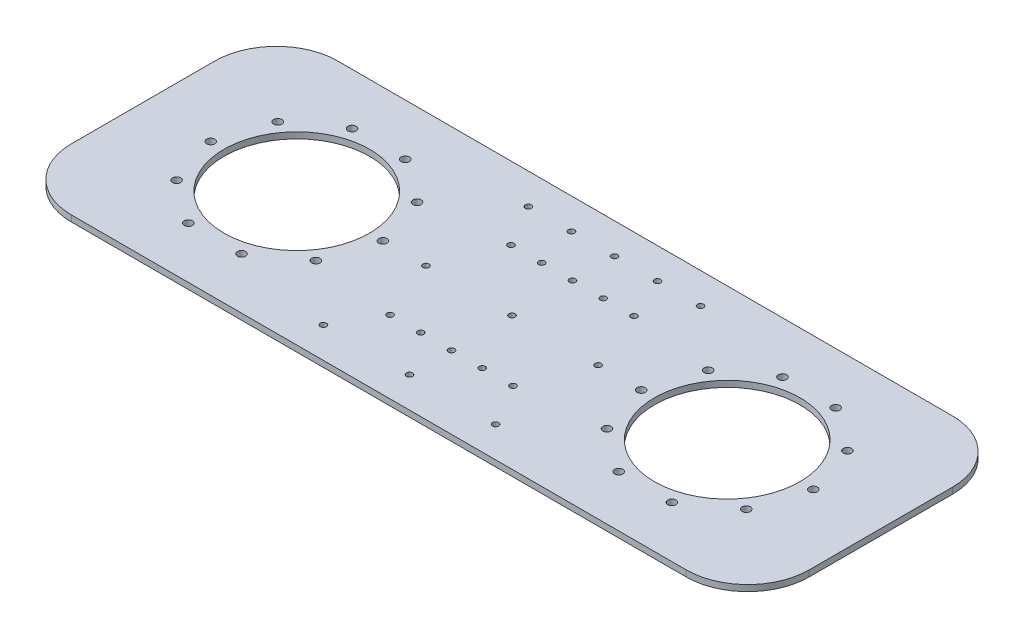
SolidWorks part; units mm, degrees
ref_plane "前基準面" through (0, 0, 0) normal (0, 0, 1) x (1, 0, 0)
ref_plane "上基準面" through (0, 0, 0) normal (0, 1, 0) x (1, 0, 0)
ref_plane "右基準面" through (0, 0, 0) normal (1, 0, 0) x (0, 0, -1)
sketch "草圖1" plane through (0, 0, 0) normal (0, 1, 0) x (1, 0, 0)
  line L0 (-105, 0) -> (105, 0) construction
  line L1 (-150, 65) -> (150, 65)
  line L2 (-180, 35) -> (-180, -35)
  line L3 (-150, -65) -> (150, -65)
  line L4 (180, 35) -> (180, -35)
  line L5 (-180, 65) -> (180, -65) construction
  line L6 (-180, -65) -> (180, 65) construction
  circle A0 centre (105, 0) radius 35.5
  circle A1 centre (-105, 0) radius 35.5
  arc A2 (150, 65) -> (180, 35) centre (150, 35) cw
  arc A3 (180, -35) -> (150, -65) centre (150, -35) cw
  arc A4 (-150, -65) -> (-180, -35) centre (-150, -35) cw
  arc A5 (-180, 35) -> (-150, 65) centre (-150, 35) cw
  point P0 (0, 0)
  point P22 (0, 0)
  dimension "D3" = 71
  dimension "D5" = 30
  dimension "D1" = 360
  dimension "D2" = 130
  dimension "D4" = 210
extrude "填料-伸長1" add sketch "草圖1" along normal blind 3
sketch "草圖3" plane through (0, 3, 0) normal (0, 1, 0) x (1, 0, 0)
  circle A0 centre (-105, 0) radius 42 construction
  circle A1 centre (-63, 0) radius 2
  dimension "D1" = 84
  dimension "D2" = 4
extrude "除料-伸長1" cut sketch "草圖3" against normal up to next
pattern_circular "環狀複製排列1" count 10 over 360 about axis through (-105, 0, 0) along (0, 1, 0) of "除料-伸長1"
mirror "鏡射1" about plane through (0, 0, 0) normal (1, 0, 0) of "除料-伸長1", "環狀複製排列1"
sketch "草圖4" plane through (0, 3, 0) normal (0, 1, 0) x (1, 0, 0)
  line L1 (-41, 33) -> (41, 33) construction
  line L2 (-41, 33) -> (-41, -33) construction
  line L3 (-41, -33) -> (41, -33) construction
  line L4 (41, 33) -> (41, -33) construction
  line L5 (-41, 33) -> (41, -33) construction
  line L6 (-41, -33) -> (41, 33) construction
  line L7 (-50, 54) -> (50, 54) construction
  line L8 (-50, 54) -> (-50, 46) construction
  line L9 (-50, 46) -> (50, 46) construction
  line L10 (50, 54) -> (50, 46) construction
  line L11 (-50, 54) -> (50, 46) construction
  line L12 (-50, 46) -> (50, 54) construction
  circle A0 centre (42, 50) radius 1.5
  point P0 (0, 0)
  point P6 (0, 50)
  dimension "D6" = 3
  dimension "D1" = 82
  dimension "D2" = 66
  dimension "D3" = 8
  dimension "D4" = 100
  dimension "D5" = 50
  dimension "D7" = 8
extrude "除料-伸長2" cut sketch "草圖4" against normal up to next
pattern_linear "直線複製排列1" count 5 spacing 21 along (-1, 0, 0) of "除料-伸長2"
sketch "草圖6" plane through (0, 3, 0) normal (0, 1, 0) x (1, 0, 0)
  line L1 (-41, 29.5) -> (41, 29.5) construction
  line L2 (-41, 29.5) -> (-41, -29.5) construction
  line L3 (-41, -29.5) -> (41, -29.5) construction
  line L4 (41, 29.5) -> (41, -29.5) construction
  line L5 (-41, 29.5) -> (41, -29.5) construction
  line L6 (-41, -29.5) -> (41, 29.5) construction
  circle A1 centre (30, 29.5) radius 1.5
  point P0 (0, 0)
  dimension "D3" = 3
  dimension "D1" = 59
  dimension "D2" = 82
  dimension "D4" = 11
extrude "除料-伸長3" cut sketch "草圖6" against normal up to next
pattern_linear "直線複製排列3" count 5 spacing 15 along (-1, 0, 0) of "除料-伸長3"
mirror "鏡射2" about plane through (0, 0, 0) normal (0, 0, 1) of "直線複製排列3", "除料-伸長3"
sketch "草圖7" plane through (0, 3, 0) normal (0, 1, 0) x (1, 0, 0)
  circle A0 centre (42, 0) radius 1.5
  circle A1 centre (0, 0) radius 1.5
  circle A2 centre (-42, 0) radius 1.5
  point P6 (0, 50)
  point P7 (-42, 50)
  point P8 (42, 50)
  dimension "D1" = 3
  dimension "D2" = 50
extrude "除料-伸長4" cut sketch "草圖7" against normal up to next
pattern_linear "直線複製排列4" count 2 spacing 50 along (0, 0, 1) of "除料-伸長4"
